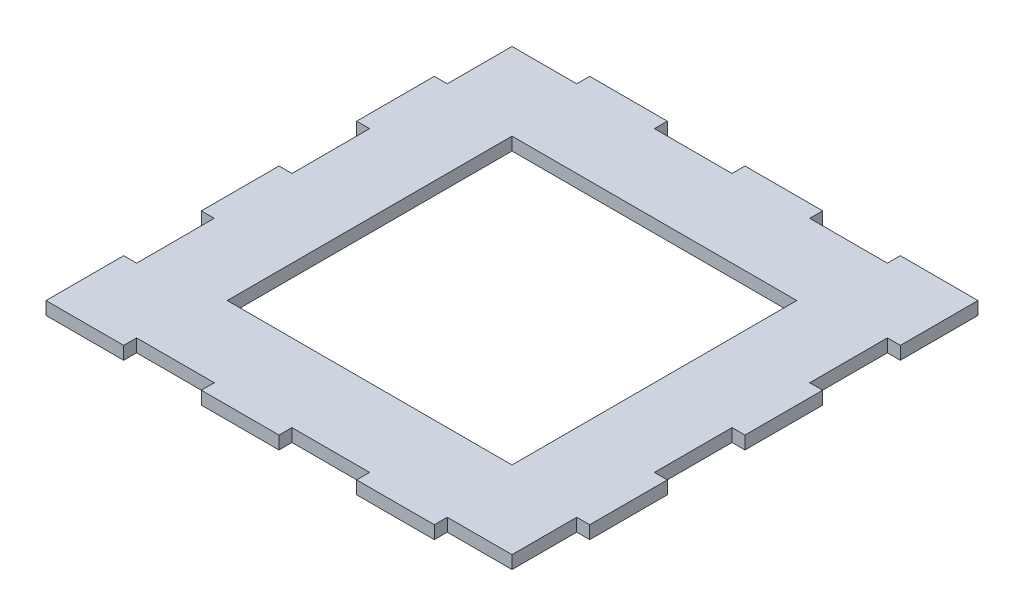
SolidWorks part; units mm, degrees
ref_plane "Front Plane" through (0, 0, 0) normal (0, 0, 1) x (1, 0, 0)
ref_plane "Top Plane" through (0, 0, 0) normal (0, 1, 0) x (1, 0, 0)
ref_plane "Right Plane" through (0, 0, 0) normal (1, 0, 0) x (0, 0, -1)
sketch "Sketch1" plane through (0, 0, 0) normal (0, 1, 0) x (1, 0, 0)
  line L1 (228.6, 228.6) -> (-228.6, 228.6)
  line L2 (228.6, 228.6) -> (228.6, -228.6)
  line L3 (228.6, -228.6) -> (-228.6, -228.6)
  line L4 (-228.6, 228.6) -> (-228.6, -228.6)
  line L5 (228.6, 228.6) -> (-228.6, -228.6) construction
  line L6 (228.6, -228.6) -> (-228.6, 228.6) construction
  line L7 (-139.7, -139.7) -> (139.7, -139.7)
  line L8 (-139.7, -139.7) -> (-139.7, 139.7)
  line L9 (-139.7, 139.7) -> (139.7, 139.7)
  line L10 (139.7, -139.7) -> (139.7, 139.7)
  line L11 (-139.7, -139.7) -> (139.7, 139.7) construction
  line L12 (-139.7, 139.7) -> (139.7, -139.7) construction
  point P0 (0, 0)
  point P5 (0, 0)
  dimension "D1" = 457.2
  dimension "D2" = 457.2
  dimension "D3" = 279.4
extrude "Boss-Extrude1" add sketch "Sketch1" along normal blind 12.7 contours L1 L4 L3 L2
sketch "Sketch2" plane through (0, 12.7, 0) normal (0, 1, 0) x (1, 0, 0)
  line L0 (-139.7, -139.7) -> (139.7, -139.7) construction
  line L1 (139.7, -139.7) -> (139.7, 139.7) construction
  line L2 (-139.7, 139.7) -> (139.7, 139.7) construction
  line L3 (-139.7, -139.7) -> (-139.7, 139.7) construction
  line L4 (-139.7, -139.7) -> (139.7, -139.7)
  line L5 (139.7, -139.7) -> (139.7, 139.7)
  line L6 (-139.7, 139.7) -> (139.7, 139.7)
  line L7 (-139.7, -139.7) -> (-139.7, 139.7)
extrude "Cut-Extrude1" cut sketch "Sketch2" against normal through all
sketch "Sketch3" plane through (0, 12.7, 0) normal (0, 1, 0) x (1, 0, 0)
  line L0 (-228.6, 215.9) -> (228.6, 215.9) construction
  line L1 (-228.6, 228.6) -> (-228.6, -228.6) construction
  line L2 (228.6, 228.6) -> (228.6, -228.6) construction
  line L3 (228.6, 228.6) -> (-228.6, 228.6) construction
  line L4 (-228.6, 228.6) -> (-152.4, 228.6)
  line L5 (-228.6, 228.6) -> (-228.6, 215.9)
  line L6 (-228.6, 215.9) -> (-152.4, 215.9)
  line L7 (-152.4, 228.6) -> (-152.4, 215.9)
  line L8 (-76.2, 228.6) -> (0, 228.6)
  line L9 (-76.2, 228.6) -> (-76.2, 215.9)
  line L10 (-76.2, 215.9) -> (0, 215.9)
  line L11 (0, 228.6) -> (0, 215.9)
  line L12 (215.9, 228.6) -> (215.9, -228.6) construction
  line L13 (76.2, 228.6) -> (152.4, 228.6)
  line L14 (76.2, 228.6) -> (76.2, 215.9)
  line L15 (76.2, 215.9) -> (152.4, 215.9)
  line L16 (152.4, 228.6) -> (152.4, 215.9)
  line L17 (228.6, -228.6) -> (-228.6, -228.6) construction
  line L18 (-228.6, -215.9) -> (228.6, -215.9) construction
  line L19 (228.6, -228.6) -> (215.9, -228.6)
  line L20 (228.6, -228.6) -> (228.6, -152.4)
  line L21 (228.6, -152.4) -> (215.9, -152.4)
  line L22 (215.9, -228.6) -> (215.9, -152.4)
  line L23 (228.6, -76.2) -> (215.9, -76.2)
  line L24 (228.6, -76.2) -> (228.6, 0)
  line L25 (228.6, 0) -> (215.9, 0)
  line L26 (215.9, -76.2) -> (215.9, 0)
  line L27 (228.6, 76.2) -> (215.9, 76.2)
  line L28 (228.6, 76.2) -> (228.6, 152.4)
  line L29 (228.6, 152.4) -> (215.9, 152.4)
  line L30 (215.9, 76.2) -> (215.9, 152.4)
  line L31 (-215.9, 228.6) -> (-215.9, -228.6) construction
  line L32 (228.6, -215.9) -> (152.4, -215.9)
  line L33 (228.6, -215.9) -> (228.6, -228.6)
  line L34 (228.6, -228.6) -> (152.4, -228.6)
  line L35 (152.4, -215.9) -> (152.4, -228.6)
  line L36 (76.2, -215.9) -> (0, -215.9)
  line L37 (76.2, -215.9) -> (76.2, -228.6)
  line L38 (76.2, -228.6) -> (0, -228.6)
  line L39 (0, -215.9) -> (0, -228.6)
  line L40 (-76.2, -215.9) -> (-152.4, -215.9)
  line L41 (-76.2, -215.9) -> (-76.2, -228.6)
  line L42 (-76.2, -228.6) -> (-152.4, -228.6)
  line L43 (-152.4, -215.9) -> (-152.4, -228.6)
  line L45 (-228.6, 228.6) -> (-215.9, 228.6)
  line L46 (-228.6, 228.6) -> (-228.6, 152.4)
  line L47 (-228.6, 152.4) -> (-215.9, 152.4)
  line L48 (-215.9, 228.6) -> (-215.9, 152.4)
  line L49 (-228.6, 76.2) -> (-215.9, 76.2)
  line L50 (-228.6, 76.2) -> (-228.6, 0)
  line L51 (-228.6, 0) -> (-215.9, 0)
  line L52 (-215.9, 76.2) -> (-215.9, 0)
  line L53 (-228.6, -76.2) -> (-215.9, -76.2)
  line L54 (-228.6, -76.2) -> (-228.6, -152.4)
  line L55 (-228.6, -152.4) -> (-215.9, -152.4)
  line L56 (-215.9, -76.2) -> (-215.9, -152.4)
  dimension "D1" = 12.7
  dimension "D2" = 76.2
  dimension "D3" = 76.2
  dimension "D4" = 76.2
  dimension "D5" = 76.2
  dimension "D6" = 76.2
  dimension "D7" = 12.7
  dimension "D8" = 76.2
  dimension "D9" = 76.2
  dimension "D10" = 76.2
  dimension "D11" = 76.2
  dimension "D12" = 76.2
  dimension "D13" = 76.2
  dimension "D14" = 76.2
  dimension "D15" = 76.2
  dimension "D16" = 76.2
  dimension "D17" = 76.2
  dimension "D18" = 12.7
  dimension "D19" = 76.2
  dimension "D20" = 76.2
  dimension "D21" = 76.2
  dimension "D22" = 76.2
  dimension "D23" = 12.7
extrude "Cut-Extrude2" cut sketch "Sketch3" against normal through all contours L5 L6 L7 L4 | L46 L47 L48 L45 | L8 L11 L10 L9 | L15 L16 L13 L14 | L28 L29 L30 L27 | L24 L25 L26 L23 | L20 L21 L22 L19 | L33 L32 L35 L34 | L36 L39 L38 L37 | L40 L43 L42 L41 | L54 L55 L56 L53 | L50 L51 L52 L49
